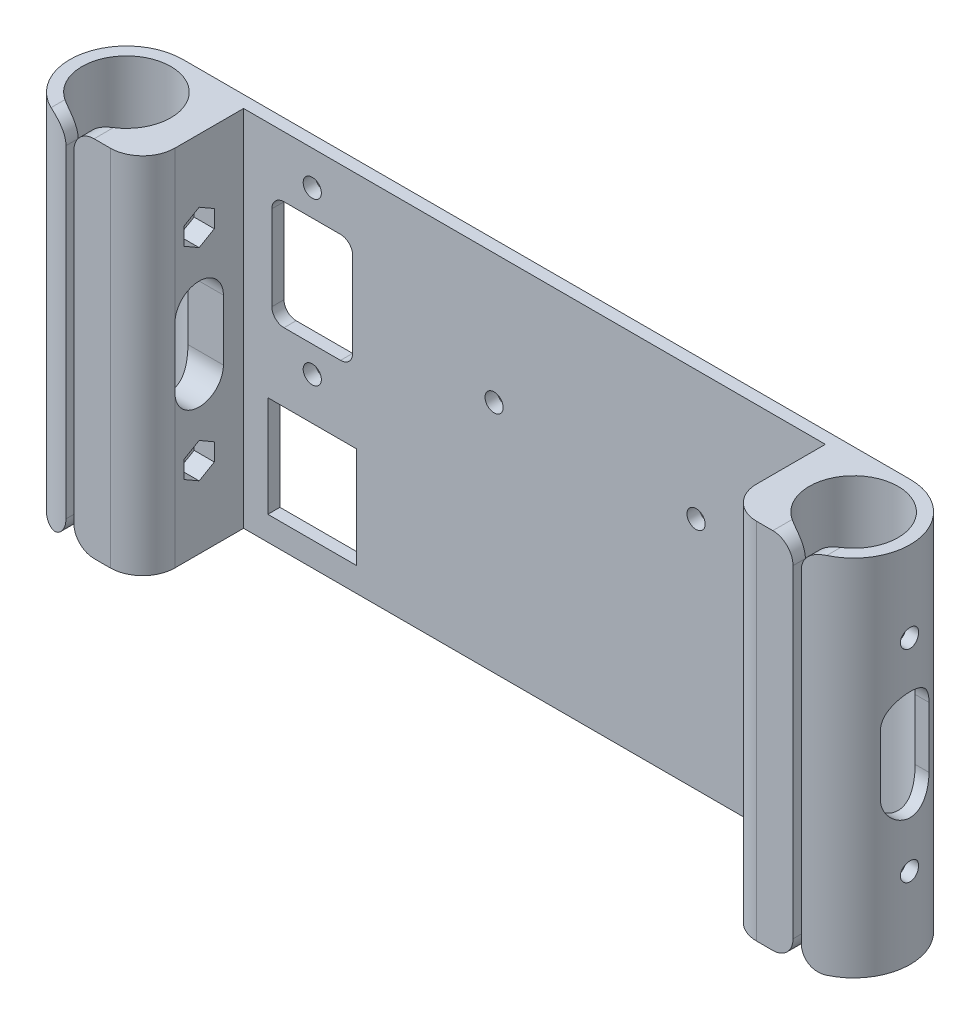
SolidWorks part; units mm, degrees
ref_plane "Front Plane" through (0, 0, 0) normal (0, 0, 1) x (1, 0, 0)
ref_plane "Top Plane" through (0, 0, 0) normal (0, 1, 0) x (1, 0, 0)
ref_plane "Right Plane" through (0, 0, 0) normal (1, 0, 0) x (0, 0, -1)
sketch "Sketch1" plane through (0, 0, 0) normal (0, 1, 0) x (1, 0, 0)
  line L0 (137.4606, -14.5) -> (119.4606, -14.5)
  line L1 (119.4606, -14.5) -> (119.4606, 10.5)
  line L2 (-42.5394, -14.5) -> (-24.5394, -14.5)
  line L3 (-42.5394, 13.5) -> (137.4606, 13.5)
  line L4 (119.4606, 10.5) -> (-24.5394, 10.5)
  line L5 (-24.5394, -14.5) -> (-24.5394, 10.5)
  circle A0 centre (-42.5394, -0.5) radius 11
  circle A1 centre (137.4606, -0.5) radius 11
  arc A2 (-42.5394, -14.5) -> (-42.5394, 13.5) centre (-42.5394, -0.5) cw
  arc A6 (137.4606, 13.5) -> (137.4606, -14.5) centre (137.4606, -0.5) cw
  dimension "D3" = 22
  dimension "D4" = 22
  dimension "D5" = 180
  dimension "D6" = 3
  dimension "D1" = 18
  dimension "D2" = 18
  dimension "D8" = 3
extrude "Boss-Extrude1" add sketch "Sketch1" along normal blind 90
fillet "Fillet1" radius 8 2 edges at (119.4606, 45, 14.5) (-24.5394, 45, 14.5)
sketch "Sketch2" plane through (0, 0, -10.5) normal (0, 0, 1) x (1, 0, 0)
  line L0 (119.4606, 58) -> (87.4606, 58) construction
  line L1 (119.4606, 90) -> (119.4606, 0) construction
  line L2 (87.4606, 58) -> (37.4606, 58) construction
  line L4 (137.4606, 90) -> (-42.5394, 90) construction
  circle A0 centre (87.4606, 58) radius 2.25
  circle A1 centre (37.4606, 58) radius 2.25
  dimension "D4" = 4.5
  dimension "D5" = 4.5
  dimension "D1" = 32
  dimension "D2" = 50
  dimension "D3" = 32
extrude "Cut-Extrude1" cut sketch "Sketch2" against normal blind 10
sketch "Sketch3" plane through (0, 0, -10.5) normal (0, 0, 1) x (1, 0, 0)
  line L1 (2.4606, 48) -> (-17.5394, 48)
  line L2 (2.4606, 48) -> (2.4606, 75)
  line L3 (2.4606, 75) -> (-17.5394, 75)
  line L4 (-17.5394, 48) -> (-17.5394, 75)
  line L5 (137.4606, 90) -> (-42.5394, 90) construction
  line L6 (-7.5394, 81.5) -> (-7.5394, 75) construction
  line L7 (-7.5394, 75) -> (-7.5394, 41.5) construction
  circle A0 centre (37.4606, 58) radius 2.25 construction
  circle A1 centre (-7.5394, 41.5) radius 2.25
  circle A2 centre (-7.5394, 81.5) radius 2.25
  point P6 (-7.5394, 48)
  point P13 (2.4606, 61.5)
  dimension "D5" = 4.5
  dimension "D6" = 4.5
  dimension "D1" = 20
  dimension "D2" = 27
  dimension "D3" = 45
  dimension "D4" = 15
  dimension "D7" = 40
  dimension "D8" = 20
extrude "Cut-Extrude2" cut sketch "Sketch3" against normal blind 10
fillet "Fillet2" radius 3 4 edges at (-17.5394, 48, -12) (-17.5394, 75, -12) (2.4606, 75, -12) (2.4606, 48, -12)
sketch "Sketch4" plane through (0, 0, -13.5) normal (0, 0, -1) x (-1, 0, 0)
  line L0 (7.5394, 41.5) -> (7.5394, 0) construction
  line L1 (-137.4606, 0) -> (42.5394, 0) construction
  line L3 (18.5394, 6) -> (-3.4606, 6)
  line L4 (18.5394, 6) -> (18.5394, 31)
  line L5 (18.5394, 31) -> (-3.4606, 31)
  line L6 (-3.4606, 6) -> (-3.4606, 31)
  line L7 (18.5394, 6) -> (-3.4606, 31) construction
  line L8 (18.5394, 31) -> (-3.4606, 6) construction
  point P5 (7.5394, 18.5)
  dimension "D1" = 22
  dimension "D2" = 25
  dimension "D3" = 6
extrude "Cut-Extrude3" cut sketch "Sketch4" against normal blind 10
sketch "Sketch5" plane through (0, 0, 14.5) normal (0, 0, 1) x (1, 0, 0)
  line L0 (-42.5394, 90) -> (-42.5394, 0)
  line L1 (137.4606, 90) -> (137.4606, 0)
extrude "Cut-Extrude-Thin1" cut sketch "Sketch5" against normal blind 10 thin thin type mid plane wall 2
fillet "Fillet3" radius 5 8 edges at (138.4606, 0, 12.9593) (136.4606, 0, 12.9772) (138.4606, 90, 12.9593) (136.4606, 90, 12.9772) (-41.5394, 90, 12.9772) (-43.5394, 90, 12.9593) (-43.5394, 0, 12.9593) (-41.5394, 0, 12.9772)
sketch "Sketch7" plane through (-24.5394, 0, 0) normal (1, 0, 0) x (0, 0, -1)
  line L0 (-0.5, 90) -> (-0.5, 0) construction
  line L1 (-6.5, 90) -> (10.5, 90) construction
  line L2 (-6.5, 0) -> (10.5, 0) construction
  line L4 (-0.5, 52.5) -> (-0.5, 37.5) construction
  line L5 (5.5, 52.5) -> (5.5, 37.5)
  line L6 (-6.5, 52.5) -> (-6.5, 37.5)
  arc A0 (5.5, 52.5) -> (-6.5, 52.5) centre (-0.5, 52.5) ccw
  arc A1 (-6.5, 37.5) -> (5.5, 37.5) centre (-0.5, 37.5) ccw
  circle A2 centre (-0.5, 70) radius 2.25
  circle A3 centre (-0.5, 20) radius 2.25
  point P9 (-0.5, 45)
  dimension "D3" = 6
  dimension "D6" = 4.5
  dimension "D7" = 4.5
  dimension "D1" = 11
  dimension "D2" = 15
  dimension "D4" = 25
  dimension "D5" = 25
extrude "Cut-Extrude4" cut sketch "Sketch7" against normal through all both and the other way through all
sketch "Sketch8" plane through (-24.5394, 0, 0) normal (1, 0, 0) x (0, 0, -1)
  line L1 (-0.5, 74.3301) -> (-4.25, 72.1651)
  line L2 (-4.25, 72.1651) -> (-4.25, 67.8349)
  line L3 (-4.25, 67.8349) -> (-0.5, 65.6699)
  line L4 (-0.5, 65.6699) -> (3.25, 67.8349)
  line L5 (3.25, 67.8349) -> (3.25, 72.1651)
  line L6 (3.25, 72.1651) -> (-0.5, 74.3301)
  line L7 (-0.5, 24.3301) -> (-4.25, 22.1651)
  line L8 (-4.25, 22.1651) -> (-4.25, 17.8349)
  line L9 (-4.25, 17.8349) -> (-0.5, 15.6699)
  line L10 (-0.5, 15.6699) -> (3.25, 17.8349)
  line L11 (3.25, 17.8349) -> (3.25, 22.1651)
  line L12 (3.25, 22.1651) -> (-0.5, 24.3301)
  circle A0 centre (-0.5, 70) radius 3.75 construction
  circle A1 centre (-0.5, 20) radius 3.75 construction
  dimension "D1" = 7.5
extrude "Cut-Extrude5" cut sketch "Sketch8" against normal blind 5
ref_plane "Plane1" through (47.4606, 0, 0) normal (1, 0, 0) x (0, 0, -1)
mirror "Mirror1" about plane through (47.4606, 0, 0) normal (1, 0, 0) of "Cut-Extrude5"
